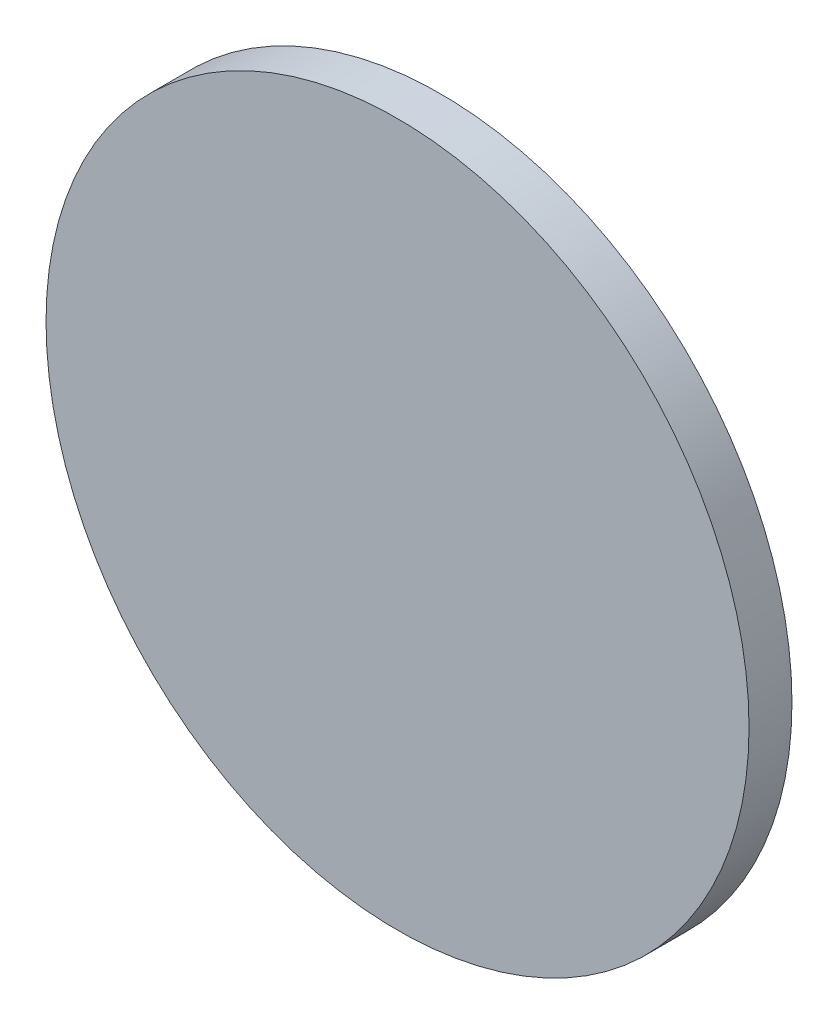
SolidWorks part; units mm, degrees
material "Acrylic (Medium-high impact)"
ref_plane "X-Y Datum" through (0, 0, 0) normal (0, 0, 1) x (1, 0, 0)
ref_plane "X-Z Datum" through (0, 0, 0) normal (0, 1, 0) x (1, 0, 0)
ref_plane "Y-Z Datum" through (0, 0, 0) normal (1, 0, 0) x (0, 0, -1)
sketch "Sketch1" plane through (0, 0, 0) normal (0, 0, 1) x (1, 0, 0)
  circle A0 centre (0, 0) radius 26
  dimension "D1" = 52
extrude "Boss-Extrude1" add sketch "Sketch1" along normal blind 3.175
